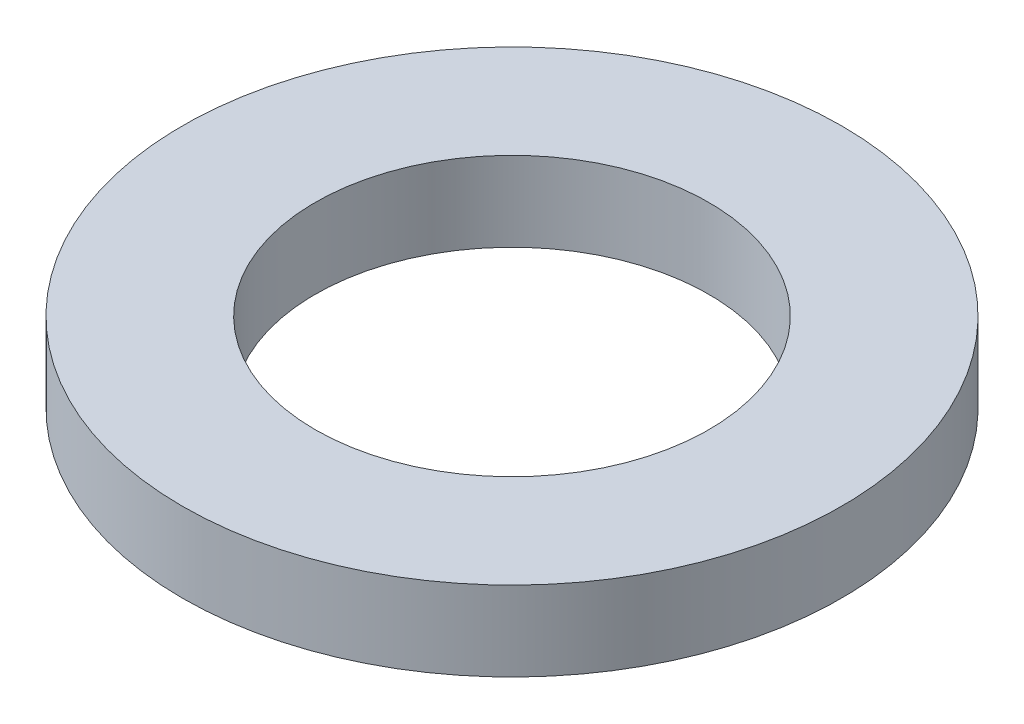
SolidWorks part; units mm, degrees
ref_plane "Front Plane" through (0, 0, 0) normal (0, 0, 1) x (1, 0, 0)
ref_plane "Top Plane" through (0, 0, 0) normal (0, 1, 0) x (1, 0, 0)
ref_plane "Right Plane" through (0, 0, 0) normal (1, 0, 0) x (0, 0, -1)
sketch "Sketch1" plane through (0, 0, 0) normal (0, 1, 0) x (1, 0, 0)
  circle A0 centre (0, 0) radius 1.8923
  dimension "OD" = 3.7846
extrude "Boss-Extrude1" add sketch "Sketch1" along normal blind 0.4572
sketch "Sketch5" plane through (0, 0.4572, 0) normal (0, 1, 0) x (-1, 0, 0)
  circle A0 centre (0, 0) radius 1.1303
  dimension "ID" = 2.2606
extrude "Cut-Extrude1" cut sketch "Sketch5" against normal through all
